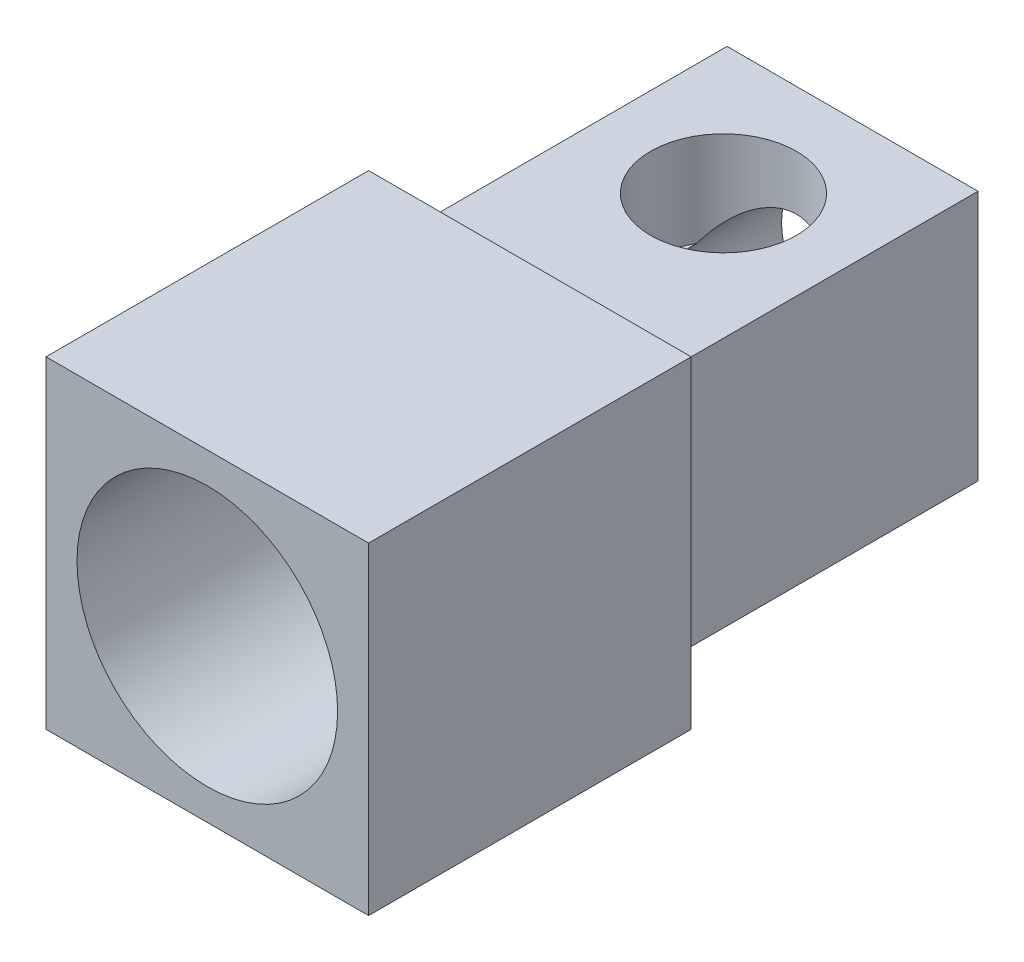
SolidWorks part; units mm, degrees
ref_plane "Front Plane" through (0, 0, 0) normal (0, 0, 1) x (1, 0, 0)
ref_plane "Top Plane" through (0, 0, 0) normal (0, 1, 0) x (1, 0, 0)
ref_plane "Right Plane" through (0, 0, 0) normal (1, 0, 0) x (0, 0, -1)
sketch "Sketch1" plane through (0, 0, 0) normal (0, 0, 1) x (1, 0, 0)
  line L1 (-5.913, 2.2391) -> (-0.913, 2.2391)
  line L2 (-5.913, 2.2391) -> (-5.913, -2.7609)
  line L3 (-5.913, -2.7609) -> (-0.913, -2.7609)
  line L4 (-0.913, 2.2391) -> (-0.913, -2.7609)
  dimension "D1" = 5
extrude "Boss-Extrude1" add sketch "Sketch1" along normal blind 10
sketch "10-32 hole for luer screw" plane through (0, 0, 10) normal (0, 0, 1) x (1, 0, 0)
  line L0 (-5.913, 2.2391) -> (-0.913, -2.7609) construction
  circle A0 centre (-3.413, -0.2609) radius 2.0193
  point P4 (-3.413, -0.2609)
  dimension "D1" = 4.0386
sketch "hole for tubing" plane through (0, 0, 0) normal (0, 0, -1) x (-1, 0, 0)
  line L0 (0.913, 2.2391) -> (5.913, -2.7609) construction
  circle A0 centre (3.413, -0.2609) radius 1.1
  point P4 (3.413, -0.2609)
  dimension "D1" = 2.2
extrude "Cut-Extrude1" cut sketch "hole for tubing" against normal through all
extrude "Cut-Extrude2" cut sketch "10-32 hole for luer screw" against normal blind 4
sketch "4-40 set screw hole" plane through (0, 2.2391, 0) normal (0, 1, 0) x (1, 0, 0)
  line L0 (-0.913, 0) -> (-5.913, -4) construction
  line L1 (-5.913, -10) -> (-5.913, 0) construction
  circle A0 centre (-3.413, -2) radius 1.1303
  dimension "D2" = 2.2606
  dimension "D1" = 4
extrude "Cut-Extrude3" cut sketch "4-40 set screw hole" against normal blind 2
sketch "Sketch2" plane through (0, 0, 0) normal (0, 0, -1) x (-1, 0, 0)
  line L0 (0.913, -2.7609) -> (5.913, 2.2391) construction
  line L1 (1.4685, -2.2054) -> (5.3576, -2.2054)
  line L2 (1.4685, -2.2054) -> (1.4685, 1.6837)
  line L3 (1.4685, 1.6837) -> (5.3576, 1.6837)
  line L4 (5.3576, -2.2054) -> (5.3576, 1.6837)
  line L5 (5.3576, -2.2054) -> (1.4685, 1.6837) construction
  line L7 (0, -3.9595) -> (7.0377, -3.9595)
  line L8 (0, -3.9595) -> (0, 4.2272)
  line L9 (0, 4.2272) -> (7.0377, 4.2272)
  line L10 (7.0377, -3.9595) -> (7.0377, 4.2272)
  point P8 (3.413, -0.2609)
  point P9 (3.413, -0.2609)
  dimension "D1" = 5.5
extrude "Cut-Extrude4" cut sketch "Sketch2" against normal blind 5
